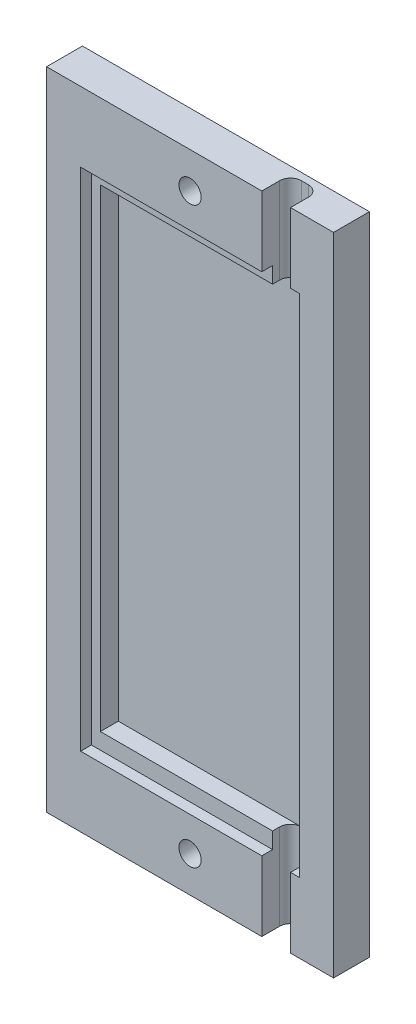
SolidWorks part; units mm, degrees
ref_plane "Front Plane" through (0, 0, 0) normal (1, 0, 0) x (0, 1, 0)
ref_plane "Top Plane" through (0, 0, 0) normal (0, 0, 1) x (0, 1, 0)
ref_plane "Right Plane" through (0, 0, 0) normal (0, 1, 0) x (-1, 0, 0)
sketch "Sketch1" plane through (0, 0, 0) normal (0, 0, 1) x (0, 1, 0)
  line L1 (0, 0) -> (90, 0)
  line L2 (0, 0) -> (0, 40)
  line L3 (0, 40) -> (90, 40)
  line L4 (90, 0) -> (90, 40)
  dimension "D1" = 40
  dimension "D2" = 90
extrude "Boss-Extrude1" add sketch "Sketch1" along normal blind 5
sketch "Sketch2" plane through (0, 0, 5) normal (0, 0, 1) x (1, 0, 0)
  line L0 (-20, 90) -> (-20, 0) construction
  line L1 (0, 90) -> (-40, 90) construction
  line L2 (-40, 0) -> (0, 0) construction
  line L3 (-35.25, 80.25) -> (-35.25, 9.75)
  line L4 (-35.25, 80.25) -> (-4.75, 80.25)
  line L5 (-35.25, 9.75) -> (-4.75, 9.75)
  line L6 (-4.75, 80.25) -> (-4.75, 9.75)
  line L7 (-35.25, 80.25) -> (-4.75, 9.75) construction
  line L8 (-35.25, 9.75) -> (-4.75, 80.25) construction
  point P6 (-20, 45)
  point P7 (-20, 45)
  dimension "D1" = 30.5
  dimension "D2" = 70.5
extrude "Cut-Extrude1" cut sketch "Sketch2" against normal blind 1.5
sketch "Sketch3" plane through (0, 0, 3.5) normal (0, 0, 1) x (1, 0, 0)
  line L0 (-20, 80.25) -> (-20, 9.75) construction
  line L1 (-4.75, 80.25) -> (-35.25, 80.25) construction
  line L2 (-35.25, 9.75) -> (-4.75, 9.75) construction
  line L3 (-34, 78) -> (-34, 12)
  line L4 (-34, 78) -> (-6, 78)
  line L5 (-34, 12) -> (-6, 12)
  line L6 (-6, 78) -> (-6, 12)
  line L7 (-34, 78) -> (-6, 12) construction
  line L8 (-34, 12) -> (-6, 78) construction
  point P6 (-20, 45)
  point P7 (-20, 45)
  dimension "D1" = 66
  dimension "D2" = 28
extrude "Cut-Extrude2" cut sketch "Sketch3" against normal blind 2.5
sketch "Sketch4" plane through (0, 0, 0) normal (0, -1, 0) x (1, 0, 0)
  line L0 (-40, 5) -> (0, 5) construction
  line L1 (-6, 5) -> (-10, 5)
  line L2 (-6, 5) -> (-6, 1)
  line L3 (-6, 1) -> (-10, 1)
  line L4 (-10, 5) -> (-10, 1)
  line L5 (0, 5) -> (0, 0) construction
  dimension "D1" = 6
  dimension "D2" = 4
  dimension "D3" = 4
extrude "Cut-Extrude3" cut sketch "Sketch4" against normal through all
fillet "Fillet1" radius 1.5 3 edges at (-10, 6, 1) (-10, 84, 1) (-6, 45, 1)
sketch "Sketch6" plane through (0, 0, 5) normal (0, 0, 1) x (1, 0, 0)
  line L0 (-10, 90) -> (-40, 90) construction
  line L1 (-40, 90) -> (-40, 0) construction
  circle A0 centre (-20, 85) radius 1.55
  dimension "D1" = 3.1
  dimension "D2" = 5
  dimension "D3" = 20
extrude "Cut-Extrude5" cut sketch "Sketch6" against normal blind 4.5
sketch "Sketch7" plane through (0, 0, 5) normal (0, 0, 1) x (1, 0, 0)
  line L0 (-40, 0) -> (-10, 0) construction
  line L1 (-40, 90) -> (-40, 0) construction
  circle A0 centre (-20, 5) radius 1.55
  dimension "D1" = 3.1
  dimension "D2" = 5
  dimension "D3" = 20
extrude "Cut-Extrude6" cut sketch "Sketch7" against normal blind 4.5
